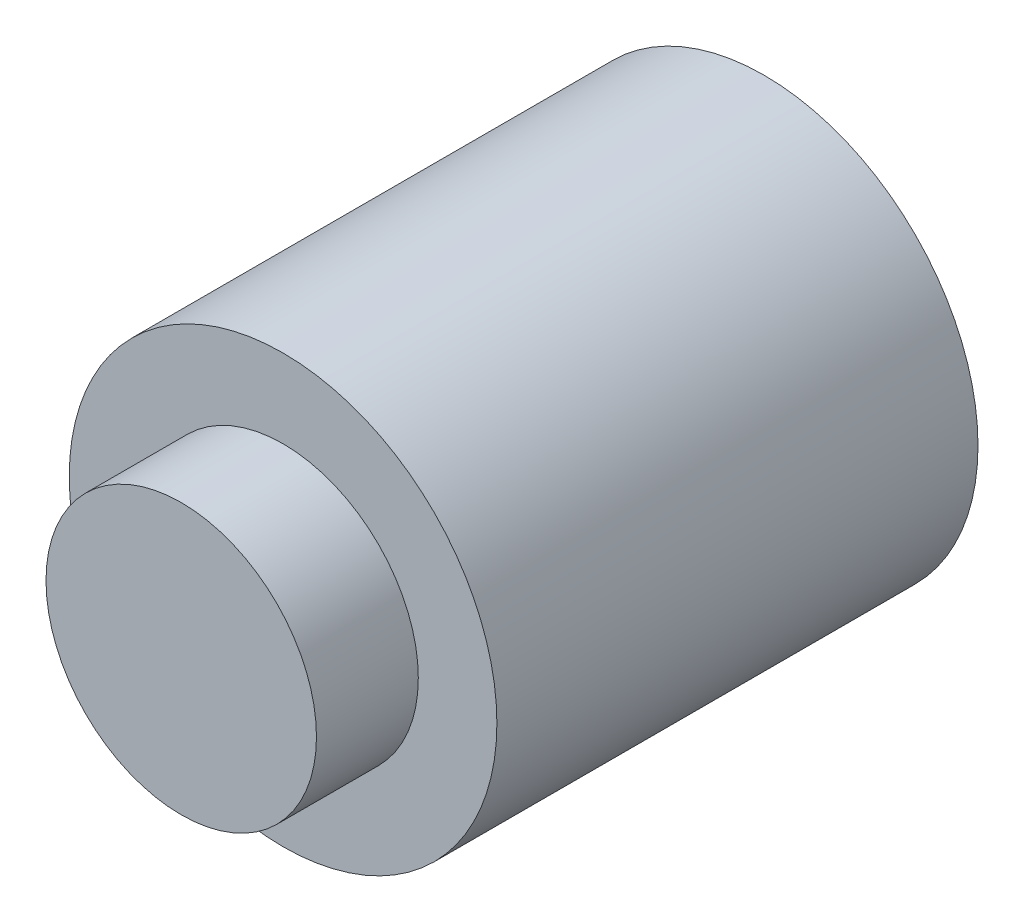
SolidWorks part; units mm, degrees
ref_plane "Front Plane" through (0, 0, 0) normal (0, 0, 1) x (1, 0, 0)
ref_plane "Top Plane" through (0, 0, 0) normal (0, 1, 0) x (1, 0, 0)
ref_plane "Right Plane" through (0, 0, 0) normal (1, 0, 0) x (0, 0, -1)
sketch "Sketch1" plane through (0, 0, 0) normal (1, 0, 0) x (0, 0, -1)
  line L0 (0, 0) -> (0, 12.6492)
  line L1 (0, 12.6492) -> (9.525, 12.6492)
  line L2 (9.525, 12.6492) -> (9.525, 20)
  line L3 (9.525, 20) -> (54.525, 20)
  line L4 (54.525, 20) -> (54.525, 13.8868)
  line L5 (54.525, 13.8868) -> (49.525, 11)
  line L6 (49.525, 11) -> (19.525, 11)
  line L7 (19.525, 11) -> (19.525, 0)
  line L8 (19.525, 0) -> (0, 0)
  point P10 (19.525, 14)
  dimension "D1" = 12.6492
  dimension "D2" = 20
  dimension "D3" = 45
  dimension "D4" = 11
  dimension "D5" = 9.525
  dimension "D6" = 30
  dimension "D7" = 5
  dimension "D8" = 120
revolve "Revolve1" add sketch "Sketch1" angle 360 about L8
sketch "Sketch2" plane through (0, 0, -54.525) normal (0, 0, -1) x (-1, 0, 0)
  line L0 (0.2238, 16.826) -> (0, -16.8275) construction
  line L1 (-16.8275, 0) -> (16.8275, 0) construction
  circle A0 centre (0, 0) radius 16.8275 construction
  point P3 (0.2238, 16.826)
  point P4 (0, -16.8275)
  point P5 (-16.8275, 0)
  point P6 (16.8275, 0)
  dimension "D1" = 33.655
hole_wizard "#4-40 Tapped Hole1" positions "Sketch2" profile "Sketch4" tap size "#4-40" standard "ANSI Inch"
sketch "Sketch4" plane through (-16.8275, 0, -54.525) normal (1, 0, 0) x (0, 1, 0)
  line L0 (0, 0) -> (0, 10.2042)
  line L1 (0, 10.2042) -> (1.1303, 9.525)
  line L2 (1.1303, 9.525) -> (1.1303, 0)
  line L5 (1.1303, 0) -> (0, 0)
  line L10 (0, 10.2042) -> (-1.1303, 9.525) construction
  line L11 (0, -6.35) -> (0, 107.95) construction
  dimension "Tap Drill Dia." = 2.2606
  dimension "Tap Drill Depth" = 9.525
  dimension "Drill Angle" = 118
cosmetic thread "Hole Thread1" parameters "D1"=5.6896, "D2"=2.8448
cosmetic thread "Hole Thread2" parameters "D1"=5.6896, "D2"=2.8448
cosmetic thread "Hole Thread3" parameters "D1"=5.6896, "D2"=2.8448
cosmetic thread "Hole Thread4" parameters "D1"=5.6896, "D2"=2.8448
